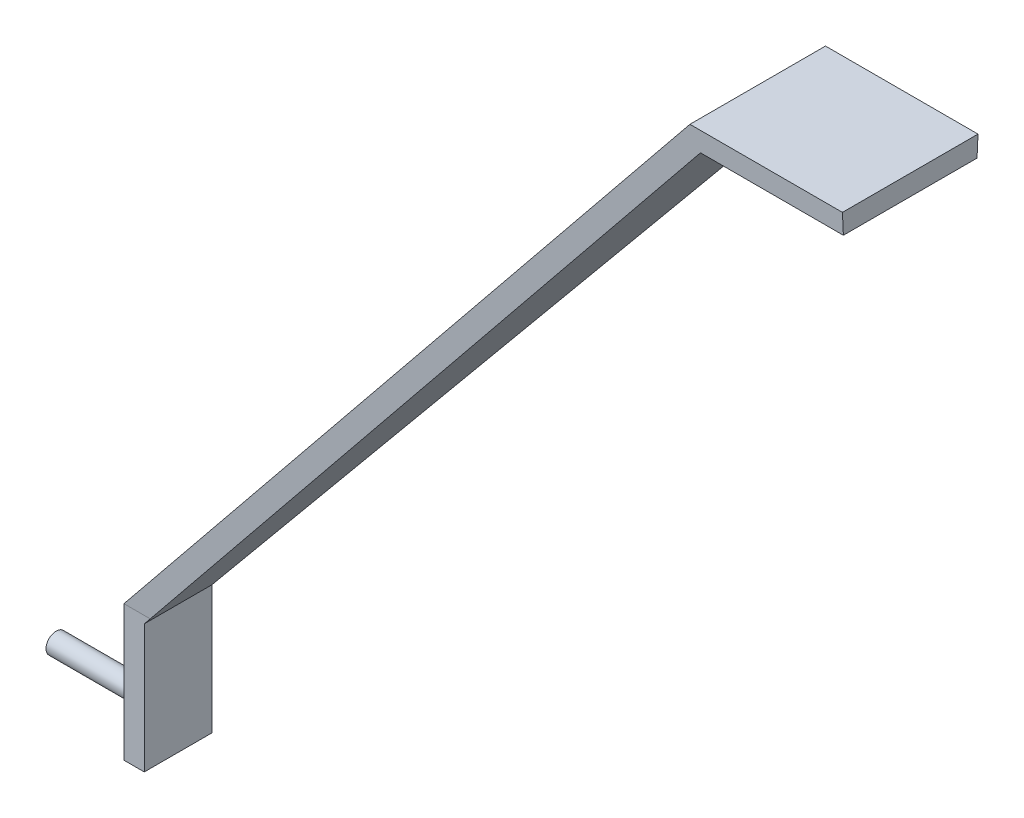
SolidWorks part; units mm, degrees
ref_plane "Front Plane" through (0, 0, 0) normal (0, 0, 1) x (1, 0, 0)
ref_plane "Top Plane" through (0, 0, 0) normal (0, 1, 0) x (1, 0, 0)
ref_plane "Right Plane" through (0, 0, 0) normal (1, 0, 0) x (0, 0, -1)
sketch "Sketch5" plane through (0, 0, 0) normal (0, 0, 1) x (1, 0, 0)
  line L0 (-42.5, 0) -> (42.5, 0)
  line L1 (42.5, 0) -> (131, -108)
  line L2 (131, -108) -> (131, -128)
  line L3 (131, -128) -> (128, -128)
  line L4 (128, -128) -> (128, -109.0722)
  line L5 (128, -109.0722) -> (41.0798, -3)
  line L6 (41.0798, -3) -> (-41.0798, -3)
  line L7 (0, -3) -> (0, 0)
  line L8 (0, 0) -> (0, -158.8716) construction
  line L9 (-128, -109.0722) -> (-41.0798, -3)
  line L10 (-128, -128) -> (-128, -109.0722)
  line L11 (-131, -128) -> (-128, -128)
  line L12 (-131, -108) -> (-131, -128)
  line L13 (-42.5, 0) -> (-131, -108)
  point P4 (131, -118)
  dimension "D1" = 3
  dimension "D2" = 3
  dimension "D3" = 3
  dimension "D4" = 125
  dimension "D5" = 105
  dimension "D6" = 42.5
  dimension "D7" = 128
extrude "Boss-Extrude1" add sketch "Sketch5" along normal blind 20 contours L0 L13 L12 L11 L10 L9 L6 L7 | L7 L6 L5 L4 L3 L2 L1 L0
sketch "Sketch6" plane through (131, 0, 0) normal (1, 0, 0) x (0, 0, -1)
  line L0 (-15, -128) -> (-15, -108)
  line L1 (-20, -128) -> (0, -128) construction
  line L2 (-20, -108) -> (0, -108) construction
  line L3 (-15, -108) -> (-20, 0)
  line L4 (-20, 0) -> (0, 0)
  line L5 (0, 0) -> (-5, -108)
  line L6 (-5, -108) -> (-5, -128)
  line L7 (-5, -128) -> (-15, -128)
  line L8 (-20, -108) -> (-20, -128) construction
  line L9 (0, -108) -> (0, -128) construction
  line L11 (0, -128) -> (-20, -128)
  line L12 (0, -128) -> (0, 0)
  line L13 (0, 0) -> (-20, 0)
  line L14 (-20, -128) -> (-20, 0)
  line M7 (0, -128) -> (0, -108)
  line M8 (0, -108) -> (-20, -108)
  line M9 (-20, -108) -> (-20, -128)
  line M10 (-20, -128) -> (0, -128)
  dimension "D1" = 5
  dimension "D2" = 5
extrude "Cut-Extrude1" cut sketch "Sketch6" against normal through all contours L0 M10 M8 M9 | L14 L3 M8 | L12 L5 M8 | L6 M8 M10 M7
sketch "Sketch7" plane through (131, 0, 0) normal (1, 0, 0) x (0, 0, -1)
  line L0 (-15, -128) -> (-5, -128) construction
  line L1 (-5, -108) -> (-5, -128) construction
  circle A0 centre (-10, -123) radius 1.5
  dimension "D1" = 3
  dimension "D2" = 5
  dimension "D3" = 5
extrude "Boss-Extrude2" add sketch "Sketch7" along normal blind 15
sketch "Sketch8" plane through (-131, 0, 0) normal (-1, 0, 0) x (0, 0, 1)
  line L0 (15, -128) -> (5, -128) construction
  line L1 (15, -128) -> (15, -108) construction
  circle A0 centre (10, -123) radius 1.5
  dimension "D1" = 3
  dimension "D2" = 5
  dimension "D3" = 5
extrude "Boss-Extrude3" add sketch "Sketch8" along normal blind 15
sketch "Sketch9" plane through (0, 0, 0) normal (1, 0, 0) x (0, 0, -1)
  line L1 (-23.3455, 7.6374) -> (44.7512, 7.6374)
  line L2 (-23.3455, 7.6374) -> (-23.3455, -150.6266)
  line L3 (-23.3455, -150.6266) -> (44.7512, -150.6266)
  line L4 (44.7512, 7.6374) -> (44.7512, -150.6266)
extrude "Cut-Extrude2" cut sketch "Sketch9" along normal blind 153
sketch "Sketch10" plane through (0, 0, 0) normal (1, 0, 0) x (0, 0, -1)
  line L1 (-23.2459, 2.4196) -> (6.2509, 2.4196)
  line L2 (-23.2459, 2.4196) -> (-23.2459, -6.7228)
  line L3 (-23.2459, -6.7228) -> (6.2509, -6.7228)
  line L4 (6.2509, 2.4196) -> (6.2509, -6.7228)
extrude "Cut-Extrude3" cut sketch "Sketch10" against normal blind 20
